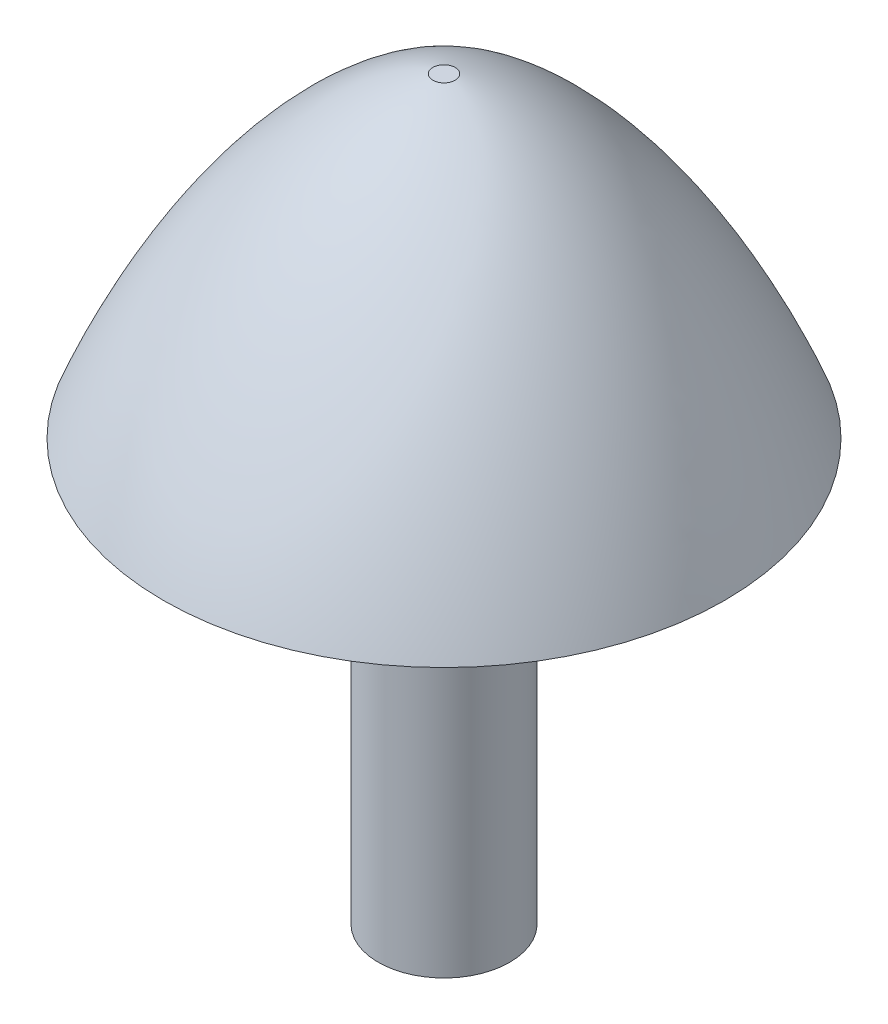
SolidWorks part; units mm, degrees
ref_plane "前视" through (0, 0, 0) normal (0, 0, 1) x (1, 0, 0)
ref_plane "上视" through (0, 0, 0) normal (0, 1, 0) x (1, 0, 0)
ref_plane "右视" through (0, 0, 0) normal (1, 0, 0) x (0, 0, -1)
sketch "草图1" plane through (0, 0, 0) normal (0, 0, 1) x (1, 0, 0)
  line L0 (0, 0) -> (0, 62.5433) construction
  line L1 (0, 0) -> (0, 31.75)
  line L2 (0.6715, 31.75) -> (0, 31.75)
  line L4 (0, 0) -> (20, 0)
  spline S0 degree 3 poles (0.6715, 31.75) (10.7603, 29.131) (19.4067, 11.2195) (20, 0) knots 0.132415 0.132415 0.132415 0.132415 1 1 1 1
  point P7 (0, 0)
  point P8 (0, 0)
  point P9 (0.6715, 31.75)
  dimension "D1" = 20
  dimension "D2" = 31.75
  dimension "D3" = 0
revolve "旋转1" add sketch "草图1" angle 360 about L0
ref_plane "基准面1" through (0, 40, 0) normal (0, -1, 0) x (-1, 0, 0)
sketch "Sketch1" plane through (0, 0, 0) normal (0, 0, 1) x (1, 0, 0)
  line L1 (-25.4422, -10.9374) -> (27.6658, -10.9374)
  line L2 (-25.4422, -10.9374) -> (-25.4422, 12.7)
  line L3 (-25.4422, 12.7) -> (27.6658, 12.7)
  line L4 (27.6658, -10.9374) -> (27.6658, 12.7)
  line L5 (-25.4422, -10.9374) -> (27.6658, 12.7) construction
  line L6 (-25.4422, 12.7) -> (27.6658, -10.9374) construction
  line L7 (-20, 0) -> (20, 0) construction
  point P0 (0, 31.75)
  point P5 (0, 31.75)
  point P6 (27.6658, -10.9374)
  point P10 (25.4422, 50.8)
  dimension "D1" = 12.7
extrude "Cut-Extrude1" cut sketch "Sketch1" against normal through all and the other way through all
sketch "Sketch5" plane through (0, 12.7, 0) normal (0, -1, 0) x (1, 0, 0)
  circle A0 centre (0, 0) radius 3.9688
  dimension "D1" = 7.9375
extrude "Boss-Extrude1" add sketch "Sketch5" along normal blind 25.4
